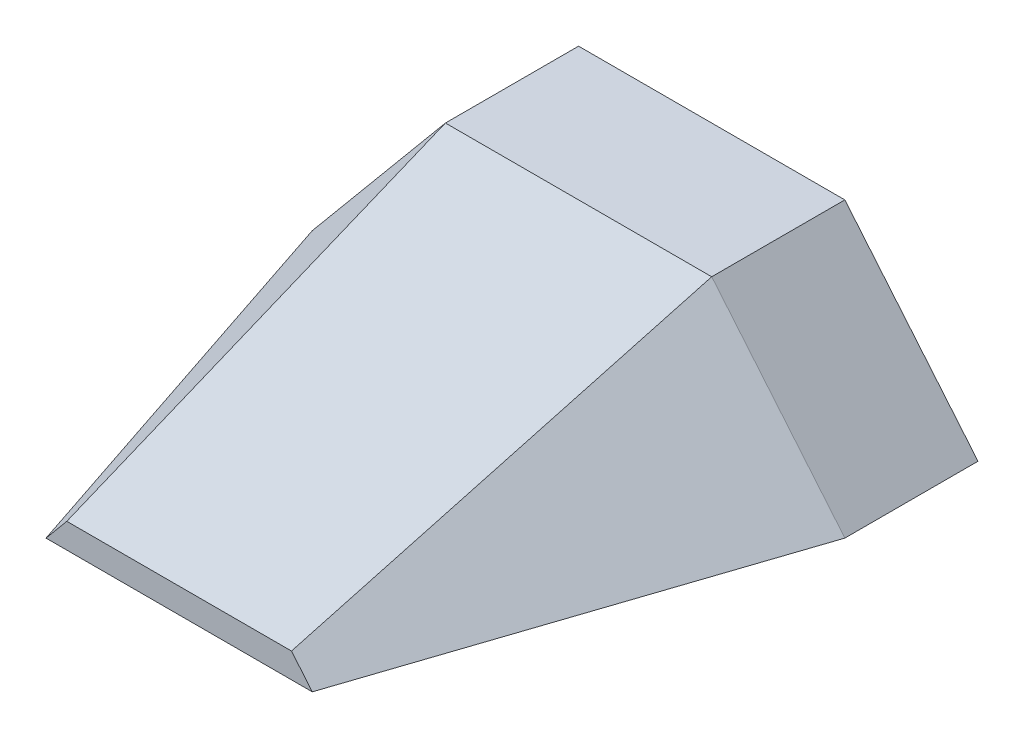
SolidWorks part; units mm, degrees
ref_plane "Front Plane" through (0, 0, 0) normal (0, 0, 1) x (1, 0, 0)
ref_plane "Top Plane" through (0, 0, 0) normal (0, 1, 0) x (1, 0, 0)
ref_plane "Right Plane" through (0, 0, 0) normal (1, 0, 0) x (0, 0, -1)
sketch "Sketch1" plane through (0, 0, 0) normal (0, 0, 1) x (1, 0, 0)
  line L0 (-8, 9.6) -> (8, 9.6)
  line L1 (8, 9.6) -> (16, 0)
  line L2 (16, 0) -> (-16, 0)
  line L3 (-16, 0) -> (-8, 9.6)
  point P2 (0, 0)
  dimension "D1" = 32
  dimension "D2" = 9.6
  dimension "D3" = 16
extrude "Boss-Extrude1" add sketch "Sketch1" along normal blind 8
ref_plane "Plane1" through (0, 0, 32) normal (0, 0, 1) x (1, 0, 0)
sketch "Sketch2" plane through (0, 0, 32) normal (0, 0, 1) x (1, 0, 0)
  line L6 (-8, 0) -> (8, 0)
  line L7 (-16, 0) -> (16, 0) construction
  line L8 (-8, 0) -> (-6.75, 1.5)
  line L9 (-6.75, 1.5) -> (6.75, 1.5)
  line L10 (6.75, 1.5) -> (8, 0)
  line L11 (0, 0) -> (0, 1.5) construction
  line L12 (-8, 9.6) -> (-16, 0) construction
  point P7 (0, 0)
  dimension "D1" = 16
  dimension "D2" = 1.5
sketch "Sketch3" plane through (0, 0, 8) normal (0, 0, 1) x (1, 0, 0)
  line L0 (-16, 0) -> (16, 0)
  line L1 (16, 0) -> (8, 9.6)
  line L2 (8, 9.6) -> (-8, 9.6)
  line L3 (-8, 9.6) -> (-16, 0)
loft "Loft1" add profiles "Sketch2" section face at (0, 4.8, 8) section "Sketch2"
shell "Shell1" thickness 1.6
